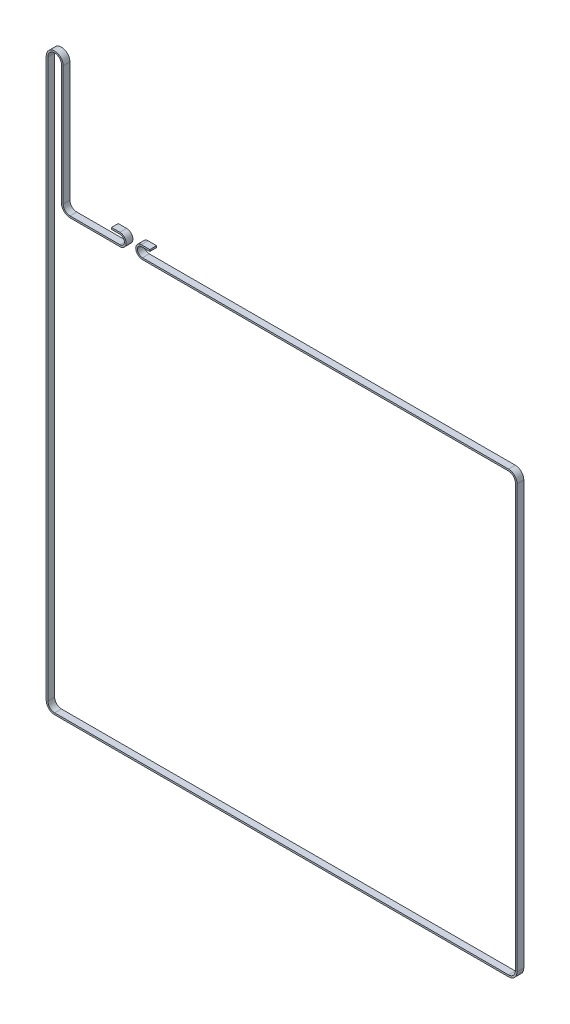
SolidWorks part; units mm, degrees
ref_plane "Front Plane" through (0, 0, 0) normal (0, 0, 1) x (1, 0, 0)
ref_plane "Top Plane" through (0, 0, 0) normal (0, 1, 0) x (1, 0, 0)
ref_plane "Right Plane" through (0, 0, 0) normal (1, 0, 0) x (0, 0, -1)
sketch "Sketch1" plane through (0, 0, 0) normal (0, 0, 1) x (1, 0, 0)
  line L0 (-6, 0) -> (-6, -494.15)
  line L1 (6, 0) -> (6, -106.1498)
  line L3 (0, -500.15) -> (402, -500.15)
  line L4 (408, -494.15) -> (408, -119.6498)
  line L5 (402, -113.6498) -> (77.764, -113.6498)
  line L7 (7.5, 0) -> (7.5, -106.1498)
  line L8 (-7.5, 0) -> (-7.5, -494.15)
  line L9 (0, -501.65) -> (402, -501.65)
  line L10 (409.5, -494.15) -> (409.5, -119.6498)
  line L11 (402, -112.1498) -> (77.7359, -112.1498)
  line L15 (84.2722, -111.1498) -> (84.2722, -104.1498) construction
  line L17 (50.2722, -104.1498) -> (50.2722, -102.6498)
  line L20 (13.5, -113.6498) -> (176.6068, -113.6498) construction
  line L21 (50.2722, -104.1498) -> (50.2722, -101.1498) construction
  line L22 (13.5, -112.1498) -> (176.6068, -112.1498) construction
  line L24 (402, -112.1498) -> (51, -112.1498) construction
  line L25 (402, -113.6498) -> (51, -113.6498) construction
  line L27 (57.7722, -112.1498) -> (13.5, -112.1498)
  line L28 (13.5, -113.6498) -> (57.7722, -113.6498)
  line L29 (84.2722, -102.6498) -> (76.7722, -102.6498)
  line L30 (84.2722, -104.1498) -> (84.2722, -102.6498)
  line L31 (76.7722, -104.1498) -> (84.2722, -104.1498)
  line L32 (50.2722, -104.1498) -> (57.7722, -104.1498)
  line L33 (50.2722, -102.6498) -> (57.7722, -102.6498)
  arc A1 (6, 0) -> (-6, 0) centre (0, 0) ccw
  arc A2 (6, -106.1498) -> (13.5, -113.6498) centre (13.5, -106.1498) ccw
  arc A3 (-6, -494.15) -> (0, -500.15) centre (0, -494.15) ccw
  arc A4 (402, -500.15) -> (408, -494.15) centre (402, -494.15) ccw
  arc A5 (408, -119.6498) -> (402, -113.6498) centre (402, -119.6498) ccw
  arc A6 (7.5, -106.1498) -> (13.5, -112.1498) centre (13.5, -106.1498) ccw
  arc A7 (7.5, 0) -> (-7.5, 0) centre (0, 0) ccw
  arc A8 (-7.5, -494.15) -> (0, -501.65) centre (0, -494.15) ccw
  arc A9 (402, -501.65) -> (409.5, -494.15) centre (402, -494.15) ccw
  arc A10 (409.5, -119.6498) -> (402, -112.1498) centre (402, -119.6498) ccw
  arc A11 (-6, -494.15) -> (0, -500.15) centre (0, -494.15) ccw construction
  arc A12 (408, -119.6498) -> (402, -113.6498) centre (402, -119.6498) ccw construction
  arc A13 (6, -106.1498) -> (13.5, -113.6498) centre (13.5, -106.1498) ccw construction
  arc A14 (402, -500.15) -> (408, -494.15) centre (402, -494.15) ccw construction
  arc A20 (57.7722, -104.1498) -> (57.7722, -112.1498) centre (57.7722, -108.1498) cw
  arc A25 (57.7722, -102.6498) -> (57.7722, -113.6498) centre (57.7722, -108.1498) cw
  arc A29 (71.7724, -107.6083) -> (77.764, -113.6498) centre (77.764, -107.658) ccw
  arc A30 (76.7722, -102.6498) -> (71.7724, -107.6083) centre (76.7722, -107.6498) ccw
  arc A31 (73.2746, -107.5204) -> (77.7359, -112.1498) centre (77.7359, -107.6855) ccw
  arc A32 (73.2746, -107.5204) -> (76.7722, -104.1498) centre (76.7722, -107.6498) cw
  dimension "D1" = 12
  dimension "D2" = 6
  dimension "D8" = 3.5
  dimension "D9" = 0.0393
  dimension "D10" = 1.5
  dimension "D11" = 7.5
  dimension "D4" = 1.5
  dimension "D5" = 1.5
  dimension "D6" = 7.5
  dimension "D7" = 6.5083
  dimension "D3" = 1.5
extrude "Boss-Extrude1" add sketch "Sketch1" along normal blind 6
